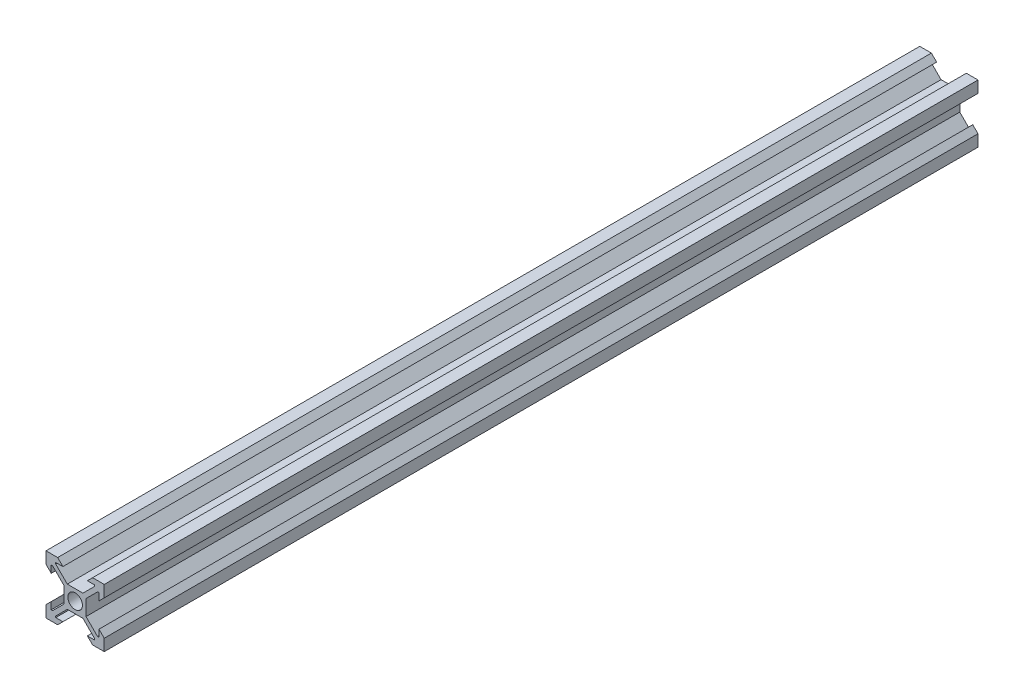
SolidWorks part; units mm, degrees
material "1060 Alloy"
ref_plane "Front Plane" through (0, 0, 0) normal (0, 0, 1) x (1, 0, 0)
ref_plane "Top Plane" through (0, 0, 0) normal (0, 1, 0) x (1, 0, 0)
ref_plane "Right Plane" through (0, 0, 0) normal (1, 0, 0) x (0, 0, -1)
sketch "Sketch1" plane through (0, 0, 0) normal (0, 0, 1) x (1, 0, 0)
  line L0 (-6, 10) -> (-4.2, 8.2)
  line L1 (-10, 10) -> (-6, 10)
  line L2 (-10, 10) -> (-10, 6)
  line L3 (-10, -10) -> (-6, -10)
  line L4 (10, 10) -> (10, 0)
  line L5 (8.2, 4.2) -> (8.2, 6.65)
  line L7 (-2.684, 3.7446) -> (2.684, 3.7446)
  line L8 (-3.7446, 2.684) -> (-3.7446, -2.684)
  line L9 (-2.684, -3.7446) -> (2.684, -3.7446)
  line L10 (3.7446, 2.684) -> (3.7446, -2.684)
  line L11 (-1.7678, 1.7678) -> (1.7678, -1.7678) construction
  line L12 (-1.7678, -1.7678) -> (1.7678, 1.7678) construction
  line L13 (-4.2, 8.2) -> (-6.6526, 8.2)
  line L14 (-7.7107, 6.65) -> (-3.7446, 2.684)
  line L15 (-1.7678, 1.7678) -> (1.7678, -1.7678) construction
  line L16 (-2.684, 3.7446) -> (2.684, 3.7446)
  line L17 (8.2, 6.65) -> (7.7107, 6.65)
  line L18 (7.7107, 6.65) -> (3.7446, 2.684)
  line L19 (6.6526, 7.7133) -> (2.684, 3.7446)
  line L20 (4.2, 8.2) -> (6, 10)
  line L21 (6, 10) -> (10, 10)
  line L22 (10, 6) -> (8.2, 4.2)
  line L23 (6.6526, 8.2) -> (6.6526, 7.7133)
  line L24 (4.2, 8.2) -> (6.6526, 8.2)
  line L25 (6, 10) -> (10, 10)
  line L26 (-10, 6) -> (-8.2, 4.2)
  line L27 (-8.2, 4.2) -> (-8.2, 6.65)
  line L28 (-6, -10) -> (-4.2, -8.2)
  line L29 (-6.6526, 7.7133) -> (-2.684, 3.7446)
  line L31 (0, 0) -> (18.3263, 0) construction
  line L32 (0, 0) -> (-13.5808, 0) construction
  line L33 (-4.2, -8.2) -> (-6.6526, -8.2)
  line L34 (-6.6526, -8.2) -> (-6.6526, -7.7133)
  line L35 (-6.6526, 8.2) -> (-6.6526, 7.7133)
  line L36 (-8.2, 6.65) -> (-7.7107, 6.65)
  line L37 (-6.6526, -7.7133) -> (-2.684, -3.7446)
  line L38 (-7.7107, -6.65) -> (-3.7446, -2.684)
  line L39 (-8.2, -6.65) -> (-7.7107, -6.65)
  line L40 (-8.2, -4.2) -> (-8.2, -6.65)
  line L41 (-10, -6) -> (-8.2, -4.2)
  line L42 (6.6526, -8.2) -> (6.6526, -7.7133)
  line L43 (4.2, -8.2) -> (6.6526, -8.2)
  line L44 (4.2, -8.2) -> (6, -10)
  line L45 (6, -10) -> (10, -10)
  line L46 (10, -6) -> (8.2, -4.2)
  line L47 (8.2, -6.65) -> (7.7107, -6.65)
  line L48 (8.2, -4.2) -> (8.2, -6.65)
  line L49 (6.6526, -7.7133) -> (2.684, -3.7446)
  line L50 (7.7107, -6.65) -> (3.7446, -2.684)
  line L51 (-10, -6) -> (-10, -10)
  line L52 (6, -10) -> (10, -10)
  line L53 (10, -6) -> (10, -10)
  circle A0 centre (0, 0) radius 2.5
  point P0 (0, 0)
  dimension "D3" = 5
  dimension "D8" = 3.7446
  dimension "D1" = 20
  dimension "D2" = 20
  dimension "D4" = 4
  dimension "D5" = 4
  dimension "D6" = 4
  dimension "D7" = 4
  dimension "D9" = 3.7446
  dimension "D10" = 2.684
  dimension "D11" = 1.8
  dimension "D12" = 6.65
  dimension "D13" = 7.7133
  dimension "D15" = 0.75
  dimension "D16" = 1.5
  dimension "D17" = 2.8284
extrude "Boss-Extrude1" add sketch "Sketch1" along normal blind 300 contours L53 L46 L48 L47 L50 L10 L18 L17 L5 L22 L4 L21 L20 L24 L23 L19 L7 L29 L35 L13 L0 L1 L2 L26 L27 L36 L14 L8 L38 L39 L40 L41 L51 L3 L28 L33 L34 L37 L9 L49 L42 L43 L44 L45 A0
